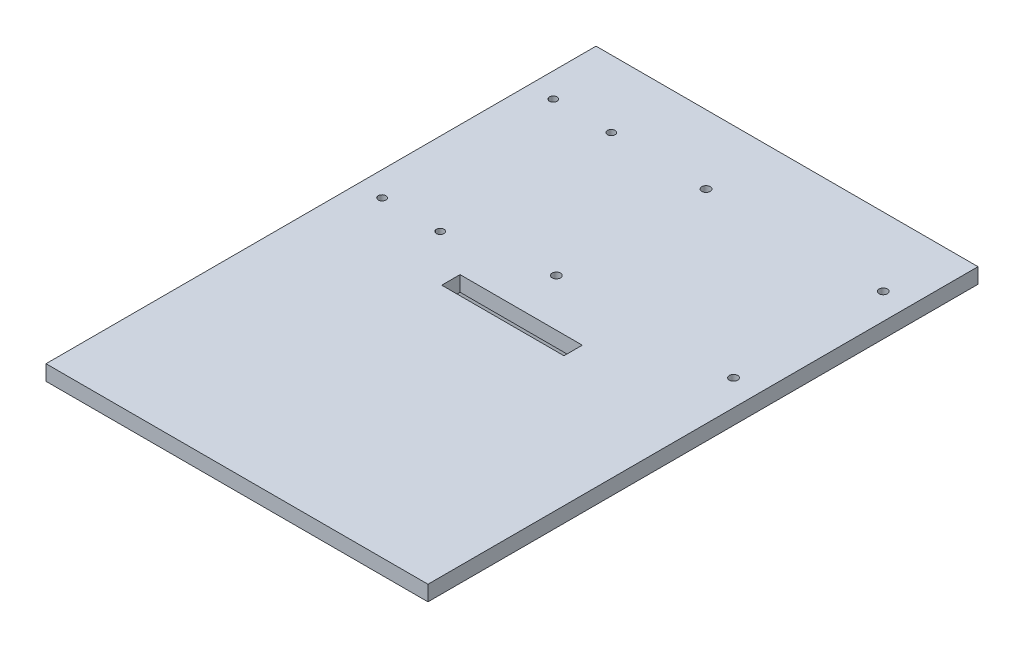
SolidWorks part; units mm, degrees
ref_plane "Front" through (0, 0, 0) normal (0, 0, 1) x (1, 0, 0)
ref_plane "Top" through (0, 0, 0) normal (0, 1, 0) x (1, 0, 0)
ref_plane "Right" through (0, 0, 0) normal (1, 0, 0) x (0, 0, -1)
sketch "Esquisse1" plane through (0, 0, 0) normal (0, 1, 0) x (1, 0, 0)
  line L1 (-31, 6) -> (31, 6)
  line L2 (-31, 6) -> (-31, -6)
  line L3 (-31, -6) -> (31, -6)
  line L4 (31, 6) -> (31, -6)
  line L5 (-31, 6) -> (31, -6) construction
  line L6 (-31, -6) -> (31, 6) construction
  line L7 (-29, 4) -> (29, 4)
  line L8 (-29, 4) -> (-29, -4)
  line L9 (-29, -4) -> (29, -4)
  line L10 (29, 4) -> (29, -4)
  line L11 (-29, 4) -> (29, -4) construction
  line L12 (-29, -4) -> (29, 4) construction
  point P0 (0, 0)
  point P6 (0, 0)
  dimension "D1" = 8
  dimension "D2" = 12
  dimension "D3" = 62
  dimension "D4" = 58
extrude "Boss.-Extru.1" add sketch "Esquisse1" along normal blind 15
sketch "Esquisse2" plane through (0, 0, 6) normal (0, 0, 1) x (1, 0, 0)
  line L0 (-31, 15) -> (31, 15) construction
  line L1 (31, 15) -> (31, 0) construction
  circle A0 centre (0, 9) radius 3.175
  dimension "D1" = 6.35
  dimension "D2" = 6
  dimension "D3" = 31
extrude "Enlèv. mat.-Extru.1" cut sketch "Esquisse2" against normal through all
sketch "Esquisse3" plane through (0, 15, 0) normal (0, 1, 0) x (1, 0, 0)
  line L1 (-62.5, 90) -> (62.5, 90)
  line L2 (-62.5, 90) -> (-62.5, -90)
  line L3 (-62.5, -90) -> (62.5, -90)
  line L4 (62.5, 90) -> (62.5, -90)
  line L5 (-62.5, 90) -> (62.5, -90) construction
  line L6 (-62.5, -90) -> (62.5, 90) construction
  point P0 (0, 0)
  dimension "D1" = 180
  dimension "D2" = 125
extrude "Boss.-Extru.2" add sketch "Esquisse3" along normal blind 5
sketch "Esquisse4" plane through (0, 20, 0) normal (0, 1, 0) x (1, 0, 0)
  line L0 (62.5, -90) -> (62.5, 90) construction
  line L1 (-52.5, -85) -> (52.5, -85) construction
  line L2 (-52.5, -85) -> (-52.5, -10) construction
  line L3 (-52.5, -10) -> (52.5, -10) construction
  line L4 (52.5, -85) -> (52.5, -10) construction
  line L5 (-52.5, -85) -> (52.5, -10) construction
  line L6 (-52.5, -10) -> (52.5, -85) construction
  line L7 (-62.5, -90) -> (62.5, -90) construction
  line L9 (-26.5, 15) -> (57.5, 15) construction
  line L10 (-26.5, 15) -> (-26.5, 71) construction
  line L11 (-26.5, 71) -> (57.5, 71) construction
  line L12 (57.5, 15) -> (57.5, 71) construction
  line L13 (-26.5, 15) -> (57.5, 71) construction
  line L14 (-26.5, 71) -> (57.5, 15) construction
  line L15 (-57.5, 9) -> (-32.5, 9) construction
  line L16 (-57.5, 9) -> (-57.5, 71) construction
  line L17 (-57.5, 71) -> (-32.5, 71) construction
  line L18 (-32.5, 9) -> (-32.5, 71) construction
  line L19 (-57.5, 9) -> (-32.5, 71) construction
  line L20 (-57.5, 71) -> (-32.5, 9) construction
  line L22 (-62.5, 90) -> (-62.5, -90) construction
  point P4 (0, -47.5)
  point P10 (0, -90)
  point P15 (15.5, 43)
  point P21 (-45, 40)
  point P22 (62.5, 0)
  dimension "D1" = 75
  dimension "D2" = 105
  dimension "D3" = 5
  dimension "D4" = 56
  dimension "D5" = 84
  dimension "D6" = 5
  dimension "D7" = 62
  dimension "D8" = 25
  dimension "D9" = 5
  dimension "D10" = 15
sketch "Esquisse6" plane through (0, 15, 0) normal (0, -1, 0) x (-1, 0, 0)
  line L0 (-29, -4) -> (-29, 4) construction
  line L1 (20, 3) -> (-20, 3)
  line L2 (20, 3) -> (20, -3)
  line L3 (20, -3) -> (-20, -3)
  line L4 (-20, 3) -> (-20, -3)
  line L5 (20, 3) -> (-20, -3) construction
  line L6 (20, -3) -> (-20, 3) construction
  line L7 (29, -4) -> (-29, -4) construction
  point P4 (0, 0)
  point P5 (0, 0)
  point P8 (-29, 0)
  point P9 (0, 0)
  point P12 (0, -4)
  dimension "D1" = 6
  dimension "D2" = 40
extrude "Enlèv. mat.-Extru.3" cut sketch "Esquisse6" against normal up to next
sketch "Esquisse8" plane through (0, 20, 0) normal (0, 1, 0) x (1, 0, 0)
  line L0 (-26.5, 71) -> (57.5, 71) construction
  line L1 (57.5, 15) -> (57.5, 71) construction
  circle A0 centre (54, 67.5) radius 1.375
  circle A1 centre (54, 18.5) radius 1.375
  circle A2 centre (-4, 67.5) radius 1.375
  circle A3 centre (-4, 18.5) radius 1.375
  point P8 (0, 0)
  point P13 (0, 0)
  dimension "D1" = 2.75
  dimension "D4" = 2.75
  dimension "D6" = 2.75
  dimension "D8" = 2.75
  dimension "D2" = 3.5
  dimension "D3" = 3.5
  dimension "D5" = 49
  dimension "D7" = 58
extrude "Enlèv. mat.-Extru.4" cut sketch "Esquisse8" against normal through all and the other way through all
sketch "Esquisse9" plane through (0, 20, 0) normal (0, 1, 0) x (1, 0, 0)
  line L0 (-32.5, 9) -> (-32.5, 71) construction
  line L1 (-57.5, 71) -> (-32.5, 71) construction
  circle A0 centre (-35.5, 68) radius 1.25
  circle A1 centre (-54.5, 68) radius 1.25
  circle A2 centre (-35.5, 12) radius 1.25
  circle A3 centre (-54.5, 12) radius 1.25
  point P2 (0, 0)
  point P11 (0, 0)
  point P12 (0, 0)
  dimension "D1" = 2.5
  dimension "D4" = 2.5
  dimension "D6" = 2.5
  dimension "D8" = 2.5
  dimension "D2" = 3
  dimension "D3" = 3
  dimension "D5" = 19
  dimension "D7" = 56
extrude "Enlèv. mat.-Extru.5" cut sketch "Esquisse9" against normal through all and the other way through all
